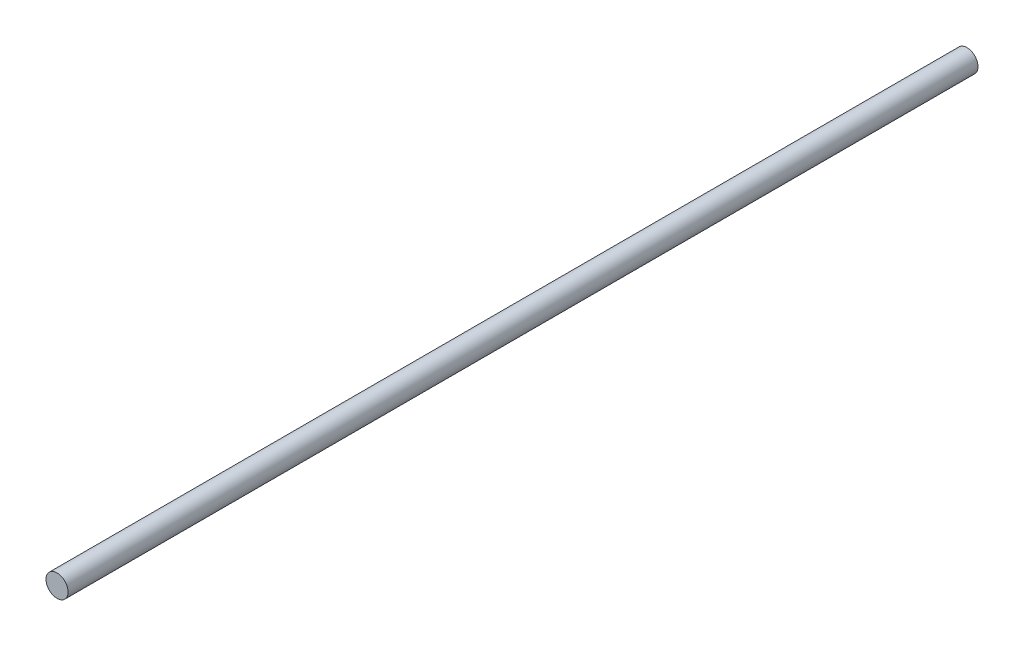
SolidWorks part; units mm, degrees
material "Хромированная нержавеющая сталь"
ref_plane "Спереди" through (0, 0, 0) normal (0, 0, 1) x (1, 0, 0)
ref_plane "Сверху" through (0, 0, 0) normal (0, 1, 0) x (1, 0, 0)
ref_plane "Справа" through (0, 0, 0) normal (1, 0, 0) x (0, 0, -1)
sketch "Эскиз1" plane through (0, 0, 0) normal (0, 1, 0) x (1, 0, 0)
  line L0 (3.75, 0) -> (0, 0)
  line L1 (0, 0) -> (0, -309)
  line L2 (0, -309) -> (3.75, -309)
  line L3 (3.75, -309) -> (3.75, 0)
  line L4 (0, 0) -> (0, -309) construction
revolve "Повернуть1" add sketch "Эскиз1" angle 360 about L4
